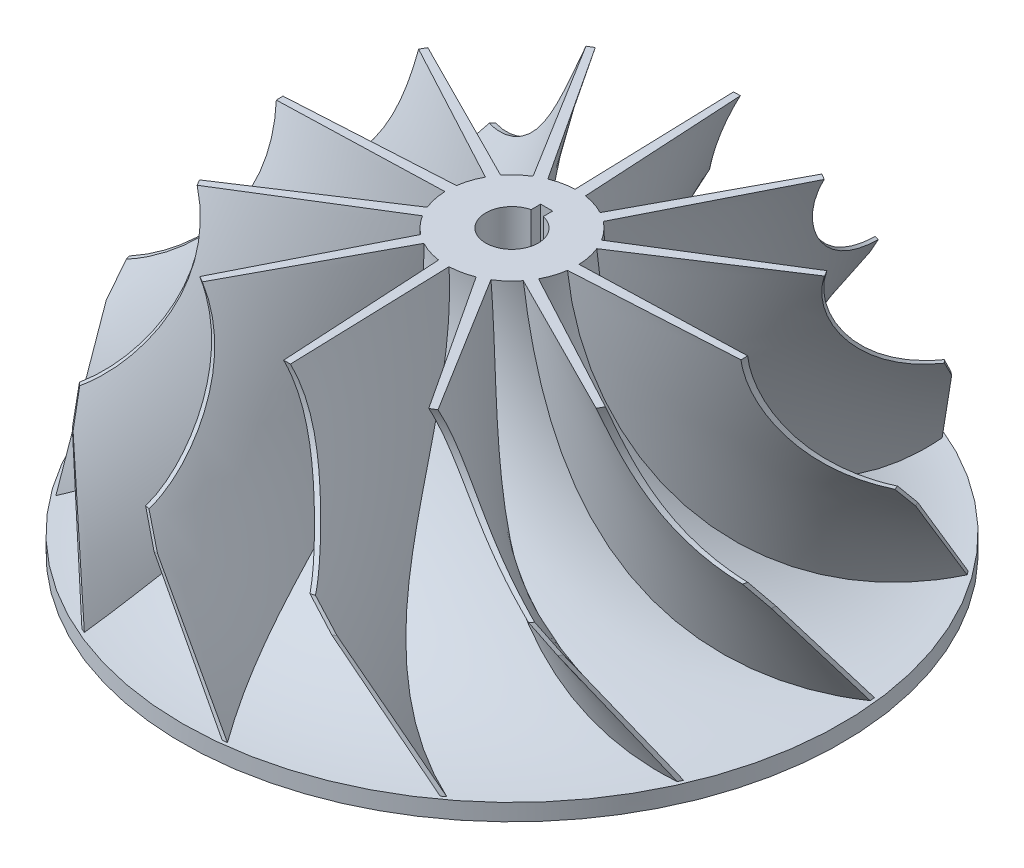
SolidWorks part; units mm, degrees
material "Alloy Steel (SS)"
ref_plane "Front Plane" through (0, 0, 0) normal (0, 0, 1) x (1, 0, 0)
ref_plane "Top Plane" through (0, 0, 0) normal (0, 1, 0) x (1, 0, 0)
ref_plane "Right Plane" through (0, 0, 0) normal (1, 0, 0) x (0, 0, -1)
sketch "Sketch1" plane through (0, 0, 0) normal (0, 0, 1) x (1, 0, 0)
  line L0 (0, 0) -> (0, 102.108)
  line L1 (0, -55) -> (0, 55) construction
  line L2 (0, 0) -> (119.634, 0)
  line L3 (0, 102.108) -> (23.622, 102.108)
  line L4 (119.634, 0) -> (119.634, 6.096)
  arc A0 (23.622, 102.108) -> (119.634, 6.096) centre (119.634, 102.108) ccw
  dimension "D1" = 102.108
  dimension "D2" = 119.634
  dimension "D3" = 23.622
  dimension "D4" = 6.096
revolve "Revolve1" add sketch "Sketch1" angle 360 about L0
ref_plane "Plane1" through (0, 0, 0) normal (0, -1, 0) x (-1, 0, 0)
sketch "Sketch4" plane through (0, 0, 0) normal (0, -1, 0) x (1, 0, 0)
  line L0 (0, 119.634) -> (0, -119.634) construction
  line L1 (0, -56.1594) -> (0, 56.1594) construction
  line L2 (-119.634, 0) -> (119.634, 0) construction
  line L3 (16.8898, 118.4358) -> (18.6357, 118.1868)
  line L4 (0, 0) -> (1.6441, 0)
  circle A0 centre (0, 0) radius 119.634 construction
  arc A1 (0, 0) -> (16.8898, 118.4358) centre (111.0133, 44.5909) cw
  arc A2 (1.6441, 0) -> (18.6357, 118.1868) centre (111.0133, 44.5909) cw
  arc A3 (1.4142, 0.568) -> (18.0888, 117.4951) centre (111.0133, 44.5909) cw construction
  dimension "D1" = 1.524
ref_plane "Plane2" through (0, 102.108, 0) normal (0, 1, 0) x (1, 0, 0)
sketch "Sketch5" plane through (0, 102.108, 0) normal (0, 1, 0) x (1, 0, 0)
  line L1 (0, 0) -> (-4.0285, 2.162)
  line L2 (0, 0) -> (-56.573, -105.4125)
  line L3 (-56.573, -105.4125) -> (-57.9112, -104.6833)
  line L4 (-4.0285, 2.162) -> (-57.9112, -104.6833)
  circle A1 centre (0, 0) radius 119.634 construction
  dimension "D1" = 4.572
  dimension "D2" = 1.524
loft "Loft1" add profiles "Sketch4", "Sketch5"
pattern_circular "CirPattern1" count 12 over 360 of "Loft1"
sketch "Sketch6" plane through (0, 0, 0) normal (0, 0, 1) x (1, 0, 0)
  line L0 (0, 0) -> (-8, 0)
  line L1 (-8.8, 0) -> (8.8, 0) construction
  line L2 (0, 0) -> (0, 102.108) construction
  line L3 (6.5447, 102.108) -> (-6.5447, 102.108) construction
  line L4 (0, -59.5114) -> (0, 59.5114) construction
  line L5 (0, 102.108) -> (-23.0807, 102.108)
  line L6 (-23.0807, 102.108) -> (-23.0807, 105.2461)
  line L7 (-23.0807, 105.2461) -> (-84.1539, 105.2461)
  line L8 (-117.4229, 6.1057) -> (-105.4125, 102.108) construction
  line L10 (0, 102.108) -> (0, 124.4525)
  line L11 (0, 124.4525) -> (-130.8247, 124.4525)
  line L12 (-130.8247, 124.4525) -> (-130.8247, -8.7284)
  line L13 (-130.8247, -8.7284) -> (0, -8.7284)
  line L14 (0, 0) -> (0, -8.7284)
  line L15 (-122.6706, 0) -> (-122.6706, 11.7686)
  line L16 (-122.6706, 11.7686) -> (-111.1029, 56.6228)
  line L18 (-94.622, 6.1057) -> (-119.5764, 102.108) construction
  line L19 (-122.6706, 0) -> (-8, 0)
  arc A1 (-84.1539, 105.2461) -> (-111.1029, 56.6228) centre (-116.8404, 91.5825) cw
  dimension "D1" = 8
revolve "Cut-Revolve1" cut sketch "Sketch6" angle 360 about L2
sketch "Sketch7" plane through (0, 0, 0) normal (0, -1, 0) x (1, 0, 0)
  circle A0 centre (0, 0) radius 25.4
  dimension "D1" = 50.8
extrude "Boss-Extrude1" [suppressed] add sketch "Sketch7" along normal blind 30
sketch "Sketch8" [suppressed] plane through (0, -30, 0) normal (0, -1, 0) x (1, 0, 0)
  circle A0 centre (0, 0) radius 12.7
  dimension "D1" = 25.4
extrude "Boss-Extrude2" [suppressed] add sketch "Sketch8" along normal blind 177.8
sketch "Sketch9" [suppressed] plane through (0, -207.8, 0) normal (0, -1, 0) x (-1, 0, 0)
  circle A0 centre (0, 0) radius 9.525
  dimension "D1" = 19.05
extrude "Boss-Extrude3" [suppressed] add sketch "Sketch9" along normal blind 254
sketch "Sketch10" plane through (0, 102.108, 0) normal (0, 1, 0) x (1, 0, 0)
  line L1 (-2.286, 12.7) -> (2.0646, 12.7)
  line L2 (-2.286, 12.7) -> (-2.286, 9.2466)
  line L4 (2.0646, 12.7) -> (2.0646, 9.2985)
  line L5 (-2.286, 12.7) -> (1.8351, 6.9762) construction
  line L6 (-1.5359, 7.1631) -> (2.0646, 12.7) construction
  arc A0 (-2.286, 9.2466) -> (2.0646, 9.2985) centre (0, 0) ccw
  point P3 (0, 9.525)
  dimension "D1" = 12.7
  dimension "D2" = 19.05
  dimension "D3" = 2.286
extrude "Cut-Extrude1" cut sketch "Sketch10" against normal through all
